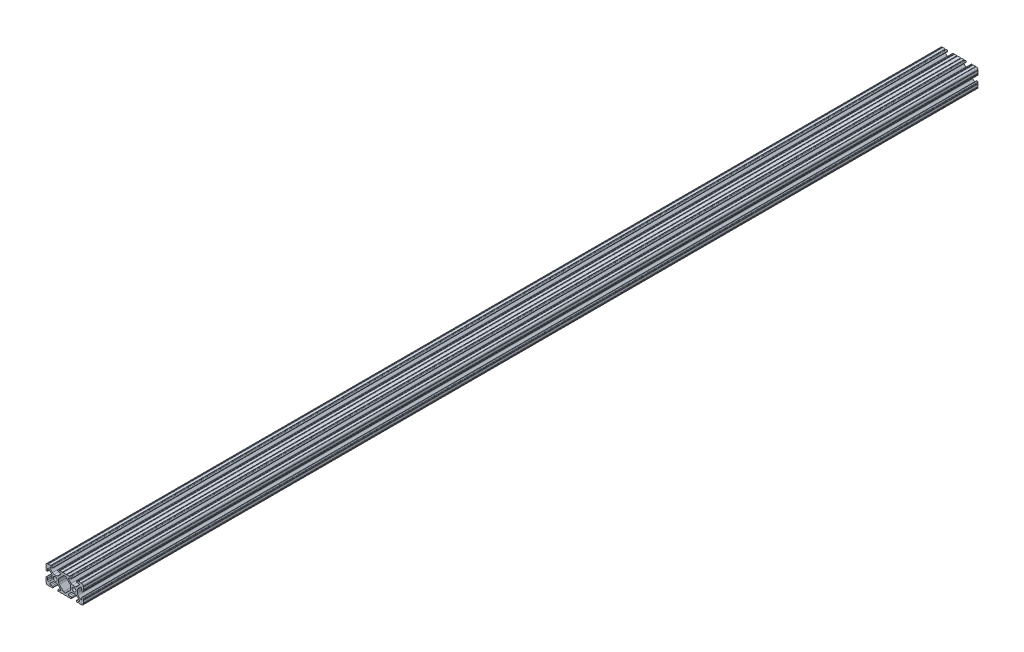
SolidWorks part; units mm, degrees
ref_plane "Front Plane" through (0, 0, 0) normal (0, 0, 1) x (1, 0, 0)
ref_plane "Top Plane" through (0, 0, 0) normal (0, 1, 0) x (1, 0, 0)
ref_plane "Right Plane" through (0, 0, 0) normal (1, 0, 0) x (0, 0, -1)
sketch "Sketch1" plane through (0, 0, 0) normal (0, 0, 1) x (1, 0, 0)
  line L0 (-7.2595, -3.8694) -> (-1.5457, -9.5728)
  line L1 (-8.1915, 1.6223) -> (-8.1915, -1.6223)
  line L2 (-1.504, 9.5765) -> (-7.252, 3.8768)
  line L3 (0.5515, 10.033) -> (-0.3952, 10.033)
  line L4 (7.2829, 3.8459) -> (1.6756, 9.5611)
  line L5 (8.1915, -1.6223) -> (8.1915, 1.6223)
  line L6 (1.5457, -9.5728) -> (7.2595, -3.8694)
  line L7 (-0.4332, -10.033) -> (0.4332, -10.033)
  line L8 (18.0171, 12.7) -> (16.9875, 12.7)
  line L9 (15.9385, 11.651) -> (15.9385, 11.5392)
  line L10 (16.9875, 10.4902) -> (19.1164, 10.4902)
  line L11 (19.8441, 8.7652) -> (16.619, 5.4551)
  line L12 (14.3449, 4.4958) -> (11.0833, 4.4958)
  line L13 (8.817, 5.4472) -> (5.5642, 8.7627)
  line L14 (6.2894, 10.4902) -> (8.4125, 10.4902)
  line L15 (9.4615, 11.5392) -> (9.4615, 11.651)
  line L16 (8.4125, 12.7) -> (7.3829, 12.7)
  line L17 (6.3669, 12.7) -> (3.1496, 12.7)
  line L18 (2.1336, 12.7) -> (-2.1336, 12.7)
  line L19 (-3.1496, 12.7) -> (-6.3669, 12.7)
  line L20 (-7.3829, 12.7) -> (-8.4125, 12.7)
  line L21 (-9.4615, 11.651) -> (-9.4615, 11.5392)
  line L22 (-8.4125, 10.4902) -> (-6.2836, 10.4902)
  line L23 (-5.5326, 8.6661) -> (-8.81, 5.4163)
  line L24 (-11.0455, 4.4958) -> (-14.3545, 4.4958)
  line L25 (-16.59, 5.4163) -> (-19.8674, 8.6661)
  line L26 (-19.1164, 10.4902) -> (-16.9875, 10.4902)
  line L27 (-15.9385, 11.5392) -> (-15.9385, 11.651)
  line L28 (-16.9875, 12.7) -> (-18.0171, 12.7)
  line L29 (-19.0331, 12.7) -> (-22.2504, 12.7)
  line L30 (-25.4, 9.5504) -> (-25.4, 6.3331)
  line L31 (-25.4, 5.3171) -> (-25.4, 4.2375)
  line L32 (-24.401, 3.2385) -> (-24.2392, 3.2385)
  line L33 (-23.1902, 4.2875) -> (-23.1902, 6.3347)
  line L34 (-21.434, 7.0665) -> (-18.148, 3.8082)
  line L35 (-17.2085, 1.5536) -> (-17.2085, -1.6952)
  line L36 (-18.1405, -3.9423) -> (-21.4316, -7.2274)
  line L37 (-23.1902, -6.498) -> (-23.1902, -4.2875)
  line L38 (-24.2392, -3.2385) -> (-24.351, -3.2385)
  line L39 (-25.4, -4.2875) -> (-25.4, -5.3171)
  line L40 (-25.4, -6.3331) -> (-25.4, -9.5504)
  line L41 (-22.2504, -12.7) -> (-19.0331, -12.7)
  line L42 (-18.0171, -12.7) -> (-16.9875, -12.7)
  line L43 (-15.9384, -11.651) -> (-15.9384, -11.5392)
  line L44 (-16.9875, -10.4902) -> (-19.1164, -10.4902)
  line L45 (-19.8341, -8.7551) -> (-16.4966, -5.4237)
  line L46 (-14.2536, -4.4958) -> (-11.1464, -4.4958)
  line L47 (-8.9034, -5.4237) -> (-5.5659, -8.7551)
  line L48 (-6.2836, -10.4902) -> (-8.4125, -10.4902)
  line L49 (-9.4616, -11.5392) -> (-9.4616, -11.651)
  line L50 (-8.4125, -12.7) -> (-7.3829, -12.7)
  line L51 (-6.3669, -12.7) -> (-3.1496, -12.7)
  line L52 (-2.1336, -12.7) -> (2.1336, -12.7)
  line L53 (3.1496, -12.7) -> (6.3669, -12.7)
  line L54 (7.3829, -12.7) -> (8.4125, -12.7)
  line L55 (9.4616, -11.651) -> (9.4616, -11.5392)
  line L56 (8.4125, -10.4902) -> (6.2894, -10.4902)
  line L57 (5.4807, -8.5353) -> (8.5979, -5.4237)
  line L58 (10.8409, -4.4958) -> (14.1026, -4.4958)
  line L59 (16.1879, -5.2766) -> (19.8682, -8.4822)
  line L60 (19.1164, -10.4902) -> (16.9875, -10.4902)
  line L61 (15.9384, -11.5392) -> (15.9384, -11.651)
  line L62 (16.9875, -12.7) -> (18.0171, -12.7)
  line L63 (19.0331, -12.7) -> (22.2504, -12.7)
  line L64 (25.4, -9.5504) -> (25.4, -6.3331)
  line L65 (25.4, -5.3171) -> (25.4, -4.2375)
  line L66 (24.401, -3.2385) -> (24.1892, -3.2385)
  line L67 (23.1902, -4.2375) -> (23.1902, -6.1559)
  line L68 (21.584, -6.8869) -> (18.2982, -4.025)
  line L69 (17.2085, -1.6308) -> (17.2085, 1.6308)
  line L70 (18.1094, 3.8465) -> (21.5263, 7.3534)
  line L71 (23.1902, 6.6769) -> (23.1902, 4.2375)
  line L72 (24.1892, 3.2385) -> (24.401, 3.2385)
  line L73 (25.4, 4.2375) -> (25.4, 5.3171)
  line L74 (25.4, 6.3332) -> (25.4, 9.5504)
  line L75 (22.2504, 12.7) -> (19.0331, 12.7)
  circle A0 centre (-12.7, 0) radius 2.6035
  circle A1 centre (12.7, 0) radius 2.6035
  arc A2 (-1.5457, -9.5728) -> (-0.4332, -10.033) centre (-0.4332, -8.4582) ccw
  arc A3 (-8.1915, -1.6223) -> (-7.2595, -3.8694) centre (-5.0165, -1.6223) ccw
  arc A4 (-7.252, 3.8768) -> (-8.1915, 1.6223) centre (-5.0165, 1.6223) ccw
  arc A5 (-0.3952, 10.033) -> (-1.504, 9.5765) centre (-0.3952, 8.4582) ccw
  arc A6 (1.6756, 9.5611) -> (0.5515, 10.033) centre (0.5515, 8.4582) ccw
  arc A7 (8.1915, 1.6223) -> (7.2829, 3.8459) centre (5.0165, 1.6223) ccw
  arc A8 (7.2595, -3.8694) -> (8.1915, -1.6223) centre (5.0165, -1.6223) ccw
  arc A9 (0.4332, -10.033) -> (1.5457, -9.5728) centre (0.4332, -8.4582) ccw
  arc A10 (18.0171, 12.7) -> (19.0331, 12.7) centre (18.5251, 12.7) ccw
  arc A11 (16.9875, 12.7) -> (15.9385, 11.651) centre (16.9875, 11.651) ccw
  arc A12 (15.9385, 11.5392) -> (16.9875, 10.4902) centre (16.9875, 11.5392) ccw
  arc A13 (19.8441, 8.7652) -> (19.1164, 10.4902) centre (19.1164, 9.4742) ccw
  arc A14 (14.3449, 4.4958) -> (16.619, 5.4551) centre (14.3449, 7.6708) ccw
  arc A15 (8.817, 5.4472) -> (11.0833, 4.4958) centre (11.0833, 7.6708) ccw
  arc A16 (6.2894, 10.4902) -> (5.5642, 8.7627) centre (6.2894, 9.4742) ccw
  arc A17 (8.4125, 10.4902) -> (9.4615, 11.5392) centre (8.4125, 11.5392) ccw
  arc A18 (9.4615, 11.651) -> (8.4125, 12.7) centre (8.4125, 11.651) ccw
  arc A19 (6.3669, 12.7) -> (7.3829, 12.7) centre (6.8749, 12.7) ccw
  arc A20 (2.1336, 12.7) -> (3.1496, 12.7) centre (2.6416, 12.7) ccw
  arc A21 (-3.1496, 12.7) -> (-2.1336, 12.7) centre (-2.6416, 12.7) ccw
  arc A22 (-7.3829, 12.7) -> (-6.3669, 12.7) centre (-6.8749, 12.7) ccw
  arc A23 (-8.4125, 12.7) -> (-9.4615, 11.651) centre (-8.4125, 11.651) ccw
  arc A24 (-9.4615, 11.5392) -> (-8.4125, 10.4902) centre (-8.4125, 11.5392) ccw
  arc A25 (-5.5326, 8.6661) -> (-6.2836, 10.4902) centre (-6.2836, 9.4235) ccw
  arc A26 (-11.0455, 4.4958) -> (-8.81, 5.4163) centre (-11.0455, 7.6708) ccw
  arc A27 (-16.59, 5.4163) -> (-14.3545, 4.4958) centre (-14.3545, 7.6708) ccw
  arc A28 (-19.1164, 10.4902) -> (-19.8674, 8.6661) centre (-19.1164, 9.4235) ccw
  arc A29 (-16.9875, 10.4902) -> (-15.9385, 11.5392) centre (-16.9875, 11.5392) ccw
  arc A30 (-15.9385, 11.651) -> (-16.9875, 12.7) centre (-16.9875, 11.651) ccw
  arc A31 (-19.0331, 12.7) -> (-18.0171, 12.7) centre (-18.5251, 12.7) ccw
  arc A32 (-23.2664, 12.6998) -> (-22.2504, 12.7) centre (-22.7584, 12.7) ccw
  arc A33 (-23.2664, 12.6998) -> (-25.3998, 10.5664) centre (-23.2918, 10.5918) ccw
  arc A34 (-25.4, 9.5504) -> (-25.3998, 10.5664) centre (-25.4, 10.0584) ccw
  arc A35 (-25.4, 5.3171) -> (-25.4, 6.3331) centre (-25.4, 5.8251) ccw
  arc A36 (-25.4, 4.2375) -> (-24.401, 3.2385) centre (-24.401, 4.2375) ccw
  arc A37 (-24.2392, 3.2385) -> (-23.1902, 4.2875) centre (-24.2392, 4.2875) ccw
  arc A38 (-21.434, 7.0665) -> (-23.1902, 6.3347) centre (-22.1596, 6.3347) ccw
  arc A39 (-17.2085, 1.5536) -> (-18.148, 3.8082) centre (-20.3835, 1.5536) ccw
  arc A40 (-18.1405, -3.9423) -> (-17.2085, -1.6952) centre (-20.3835, -1.6952) ccw
  arc A41 (-23.1902, -6.498) -> (-21.4316, -7.2274) centre (-22.1596, -6.498) ccw
  arc A42 (-23.1902, -4.2875) -> (-24.2392, -3.2385) centre (-24.2392, -4.2875) ccw
  arc A43 (-24.351, -3.2385) -> (-25.4, -4.2875) centre (-24.351, -4.2875) ccw
  arc A44 (-25.4, -6.3331) -> (-25.4, -5.3171) centre (-25.4, -5.8251) ccw
  arc A45 (-25.3998, -10.5664) -> (-25.4, -9.5504) centre (-25.4, -10.0584) ccw
  arc A46 (-25.3998, -10.5664) -> (-23.2664, -12.6998) centre (-23.2918, -10.5918) ccw
  arc A47 (-22.2504, -12.7) -> (-23.2664, -12.6998) centre (-22.7584, -12.7) ccw
  arc A48 (-18.0171, -12.7) -> (-19.0331, -12.7) centre (-18.5251, -12.7) ccw
  arc A49 (-16.9875, -12.7) -> (-15.9384, -11.651) centre (-16.9875, -11.651) ccw
  arc A50 (-15.9384, -11.5392) -> (-16.9875, -10.4902) centre (-16.9875, -11.5392) ccw
  arc A51 (-19.8341, -8.7551) -> (-19.1164, -10.4902) centre (-19.1164, -9.4742) ccw
  arc A52 (-14.2536, -4.4958) -> (-16.4966, -5.4237) centre (-14.2536, -7.6708) ccw
  arc A53 (-8.9034, -5.4237) -> (-11.1464, -4.4958) centre (-11.1464, -7.6708) ccw
  arc A54 (-6.2836, -10.4902) -> (-5.5659, -8.7551) centre (-6.2836, -9.4742) ccw
  arc A55 (-8.4125, -10.4902) -> (-9.4616, -11.5392) centre (-8.4125, -11.5392) ccw
  arc A56 (-9.4616, -11.651) -> (-8.4125, -12.7) centre (-8.4125, -11.651) ccw
  arc A57 (-6.3669, -12.7) -> (-7.3829, -12.7) centre (-6.8749, -12.7) ccw
  arc A58 (-2.1336, -12.7) -> (-3.1496, -12.7) centre (-2.6416, -12.7) ccw
  arc A59 (3.1496, -12.7) -> (2.1336, -12.7) centre (2.6416, -12.7) ccw
  arc A60 (7.3829, -12.7) -> (6.3669, -12.7) centre (6.8749, -12.7) ccw
  arc A61 (8.4125, -12.7) -> (9.4616, -11.651) centre (8.4125, -11.651) ccw
  arc A62 (9.4616, -11.5392) -> (8.4125, -10.4902) centre (8.4125, -11.5392) ccw
  arc A63 (5.4807, -8.5353) -> (6.2894, -10.4902) centre (6.2894, -9.3455) ccw
  arc A64 (10.8409, -4.4958) -> (8.5979, -5.4237) centre (10.8409, -7.6708) ccw
  arc A65 (16.1879, -5.2766) -> (14.1026, -4.4958) centre (14.1026, -7.6708) ccw
  arc A66 (19.1164, -10.4902) -> (19.8682, -8.4822) centre (19.1164, -9.3455) ccw
  arc A67 (16.9875, -10.4902) -> (15.9384, -11.5392) centre (16.9875, -11.5392) ccw
  arc A68 (15.9384, -11.651) -> (16.9875, -12.7) centre (16.9875, -11.651) ccw
  arc A69 (19.0331, -12.7) -> (18.0171, -12.7) centre (18.5251, -12.7) ccw
  arc A70 (23.2664, -12.6998) -> (22.2504, -12.7) centre (22.7584, -12.7) ccw
  arc A71 (23.2664, -12.6998) -> (25.3998, -10.5664) centre (23.2918, -10.5918) ccw
  arc A72 (25.4, -9.5504) -> (25.3998, -10.5664) centre (25.4, -10.0584) ccw
  arc A73 (25.4, -5.3171) -> (25.4, -6.3331) centre (25.4, -5.8251) ccw
  arc A74 (25.4, -4.2375) -> (24.401, -3.2385) centre (24.401, -4.2375) ccw
  arc A75 (24.1892, -3.2385) -> (23.1902, -4.2375) centre (24.1892, -4.2375) ccw
  arc A76 (21.584, -6.8869) -> (23.1902, -6.1559) centre (22.2207, -6.1559) ccw
  arc A77 (17.2085, -1.6308) -> (18.2982, -4.025) centre (20.3835, -1.6308) ccw
  arc A78 (18.1094, 3.8465) -> (17.2085, 1.6308) centre (20.3835, 1.6308) ccw
  arc A79 (23.1902, 6.6769) -> (21.5263, 7.3534) centre (22.2207, 6.6769) ccw
  arc A80 (23.1902, 4.2375) -> (24.1892, 3.2385) centre (24.1892, 4.2375) ccw
  arc A81 (24.401, 3.2385) -> (25.4, 4.2375) centre (24.401, 4.2375) ccw
  arc A82 (25.4, 6.3332) -> (25.4, 5.3171) centre (25.4, 5.8251) ccw
  arc A83 (25.3998, 10.5664) -> (25.4, 9.5504) centre (25.4, 10.0584) ccw
  arc A84 (25.3998, 10.5664) -> (23.2664, 12.6998) centre (23.2918, 10.5918) ccw
  arc A85 (22.2504, 12.7) -> (23.2664, 12.6998) centre (22.7584, 12.7) ccw
  point P248 (0, 10.033)
extrude "Boss-Extrude1" add sketch "Sketch1" along normal mid plane 1219.2
